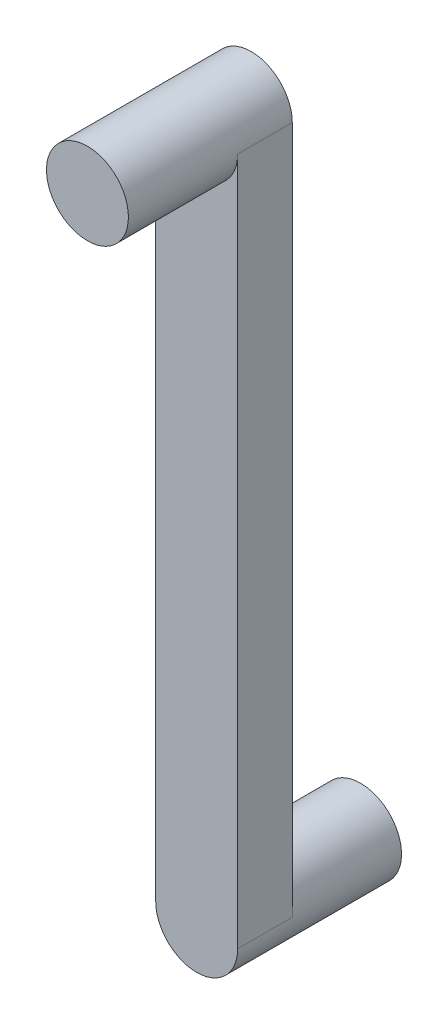
SolidWorks part; units mm, degrees
ref_plane "前视基准面" through (0, 0, 0) normal (0, 0, 1) x (1, 0, 0)
ref_plane "上视基准面" through (0, 0, 0) normal (0, 1, 0) x (1, 0, 0)
ref_plane "右视基准面" through (0, 0, 0) normal (1, 0, 0) x (0, 0, -1)
sketch "草图1" plane through (0, 0, 0) normal (0, 0, 1) x (1, 0, 0)
  line L0 (0, 0) -> (0, -126) construction
  line L1 (7.5, 0) -> (7.5, -126)
  line L2 (-7.5, 0) -> (-7.5, -126)
  arc A0 (7.5, 0) -> (-7.5, 0) centre (0, 0) ccw
  arc A1 (-7.5, -126) -> (7.5, -126) centre (0, -126) ccw
  point P3 (0, -63)
  dimension "D2" = 7.5
  dimension "D1" = 126
extrude "凸台-拉伸1" add sketch "草图1" along normal blind 10 contours A0 L2 A1 L1
sketch "草图2" plane through (0, 0, 10) normal (0, 0, 1) x (1, 0, 0)
  circle A0 centre (0, 0) radius 7.5
extrude "凸台-拉伸2" add sketch "草图2" along normal blind 20
sketch "草图3" plane through (0, 0, 0) normal (0, 0, -1) x (-1, 0, 0)
  circle A0 centre (0, -126) radius 7.5
extrude "凸台-拉伸3" add sketch "草图3" along normal blind 20
